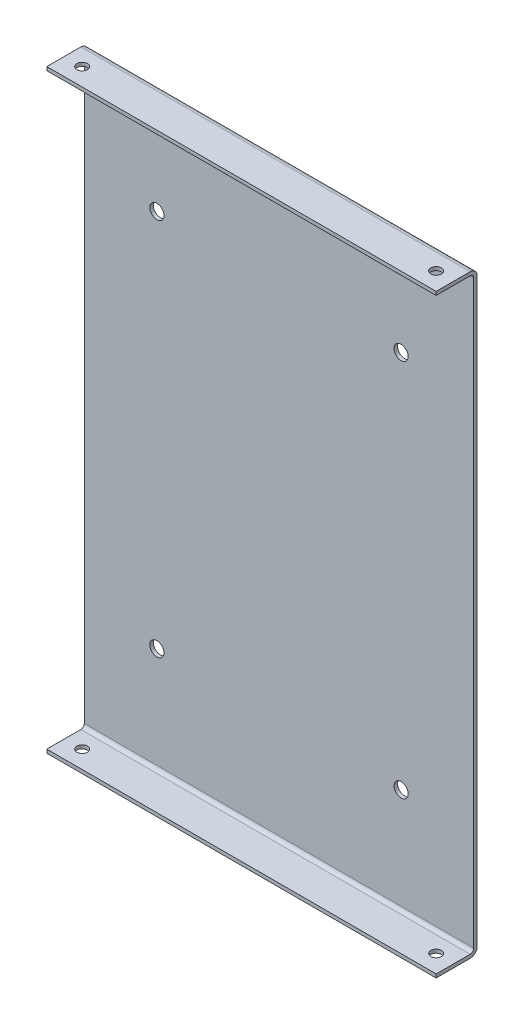
SolidWorks part; units mm, degrees
ref_plane "Plan de face" through (0, 0, 0) normal (0, 0, 1) x (1, 0, 0)
ref_plane "Plan de dessus" through (0, 0, 0) normal (0, 1, 0) x (1, 0, 0)
ref_plane "Plan de droite" through (0, 0, 0) normal (1, 0, 0) x (0, 0, -1)
sketch "Esquisse1" plane through (0, 0, 0) normal (0, 0, 1) x (1, 0, 0)
  line L1 (0, 0) -> (110, 0)
  line L2 (0, 0) -> (0, -168)
  line L3 (0, -168) -> (110, -168)
  line L4 (110, 0) -> (110, -168)
  line L5 (20.5, -30.5) -> (89.5, -30.5)
  line L6 (20.5, -30.5) -> (20.5, -137.5)
  line L7 (20.5, -137.5) -> (89.5, -137.5)
  line L8 (89.5, -30.5) -> (89.5, -137.5)
  circle A0 centre (20.5, -30.5) radius 2
  circle A1 centre (89.5, -30.5) radius 2
  circle A2 centre (89.5, -137.5) radius 2
  circle A3 centre (20.5, -137.5) radius 2
  point P13 (55, -30.5)
  point P14 (55, 0)
  point P15 (0, -84)
  point P16 (20.5, -84)
  dimension "D3" = 4
  dimension "D4" = 4
  dimension "D5" = 4
  dimension "D6" = 4
  dimension "D1" = 110
  dimension "D2" = 168
  dimension "D7" = 107
  dimension "D8" = 69
extrude "Boss.-Extru.1" add sketch "Esquisse1" along normal blind 1 contours L4 L1 L2 L3 A3 L6 A0 L5 A1 L8 A2 L7 | A3 L7 A2 L8 A1 L5 A0 L6
sketch "Esquisse2" plane through (0, 0, 1) normal (0, 0, 1) x (1, 0, 0)
  line L0 (110, 0) -> (110, -168) construction
  line L1 (0, -168) -> (110, -168)
  line L2 (0, -168) -> (0, -167)
  line L3 (0, -167) -> (110, -167)
  line L4 (110, -168) -> (110, -167)
  line L5 (0, 0) -> (0, -168) construction
  line L6 (110, 0) -> (0, 0)
  line L7 (110, 0) -> (110, -1)
  line L8 (110, -1) -> (0, -1)
  line L9 (0, 0) -> (0, -1)
  dimension "D1" = 1
  dimension "D2" = 1
extrude "Boss.-Extru.2" add sketch "Esquisse2" along normal blind 10.6
fillet "Congé1" radius 2 2 edges at (55, -168, 0) (55, 0, 0)
fillet "Congé2" radius 1 2 edges at (55, -1, 1) (55, -167, 1)
sketch "Esquisse3" plane through (0, 0, 0) normal (0, 1, 0) x (1, 0, 0)
  line L0 (105, -6.6) -> (5, -6.6)
  line L1 (110, -11.6) -> (0, -11.6) construction
  circle A0 centre (105, -6.6) radius 1.5
  circle A1 centre (5, -6.6) radius 1.5
  point P6 (55, -6.6)
  point P7 (55, -11.6)
  dimension "D1" = 3
  dimension "D2" = 3
  dimension "D3" = 100
  dimension "D4" = 5
extrude "Enlèv. mat.-Extru.1" cut sketch "Esquisse3" against normal through all
